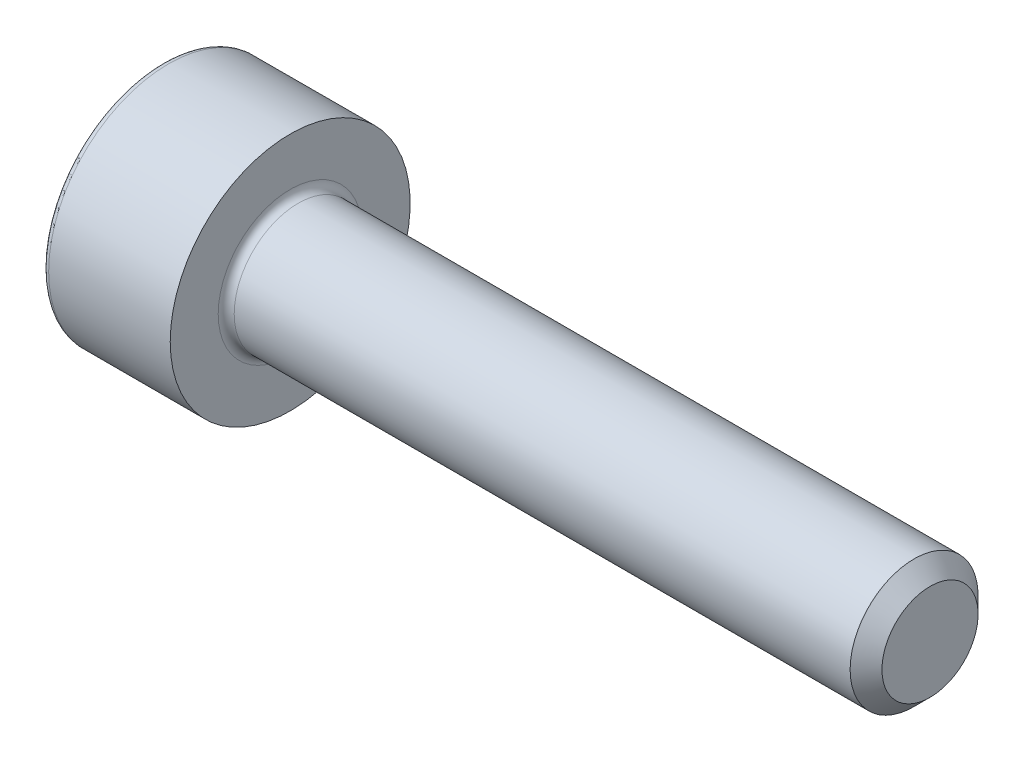
SolidWorks part; units mm, degrees
ref_plane "Front Plane" through (0, 0, 0) normal (0, 0, 1) x (1, 0, 0)
ref_plane "Top Plane" through (0, 0, 0) normal (0, 1, 0) x (1, 0, 0)
ref_plane "Right Plane" through (0, 0, 0) normal (1, 0, 0) x (0, 0, -1)
sketch "BodySke" plane through (0, 0, 0) normal (0, 0, 1) x (1, 0, 0)
  line L0 (0, 0) -> (5.8492, 0) construction
  line L1 (0, 0) -> (0, 1.5)
  line L2 (0, 1.5) -> (1.6, 1.5)
  line L3 (1.6, 1.5) -> (1.6, 0.8)
  line L4 (1.6, 0.8) -> (9.401, 0.8)
  line L5 (9.401, 0.8) -> (9.6, 0.601)
  line L6 (9.6, 0.601) -> (9.6, 0)
  line L7 (9.6, 0) -> (0, 0)
  line L8 (1.6, 0) -> (1.6, 0.601) construction
  line L9 (1.95, 1.5877) -> (1.95, 0.9267) construction
  dimension "Thread_length" = 8
  dimension "Diameter" = 1.6
  dimension "Thread_minor" = 1.202
  dimension "Body_chamfer_angle" = 45
  dimension "Length" = 8
  dimension "Head_diameter" = 3
  dimension "Head_length" = 1.6
  dimension "Advance" = 0.35
revolve "BaseBody" add sketch "BodySke" angle 360 about L0
cosmetic thread "ThreadCosmetic" [suppressed] parameters "Thread_length"=8, "Thread_minor"=1.202
fillet "Fillet1" radius 0.1 1 edges at (1.6, 0, 0.8)
fillet "Fillet2" radius 0.08 1 edges at (0, 0, 1.5)
sketch "HexSke" plane through (0, 0, 0) normal (1, 0, 0) x (0, 0, -1)
  line L1 (0, 0.866) -> (-0.75, 0.433)
  line L2 (-0.75, 0.433) -> (-0.75, -0.433)
  line L3 (-0.75, -0.433) -> (0, -0.866)
  line L4 (0, -0.866) -> (0.75, -0.433)
  line L5 (0.75, -0.433) -> (0.75, 0.433)
  line L6 (0.75, 0.433) -> (0, 0.866)
  circle A0 centre (0, 0) radius 0.75 construction
  dimension "Hex_size" = 1.5
extrude "Hex" cut sketch "HexSke" along normal blind 0.7
sketch "Hex-PreBroachSke" plane through (0, 0, 0) normal (0, 0, 1) x (1, 0, 0)
  line L0 (0, 0) -> (4.7325, 0) construction
  line L1 (0, 1.42) -> (0, -1.42) construction
  line L2 (0, 0) -> (0, 0.75)
  line L3 (0, 0.75) -> (0.7, 0.75)
  line L4 (0.7, 0.75) -> (1.133, 0)
  line L5 (1.133, 0) -> (0, 0)
  dimension "Hex_depth" = 0.7
  dimension "D1" = 1.5
  dimension "Angle" = 60
revolve "Hex-PreBroach" cut sketch "Hex-PreBroachSke" angle 360 about L0
sketch "ThdSchSke" plane through (0, 0, 0) normal (0, 0, 1) x (1, 0, 0)
  line L0 (0, 0) -> (4.4125, 0) construction
  line L1 (0, 1.42) -> (0, -1.42) construction
  line L2 (9.051, 1.0298) -> (9.051, 0.8)
  line L3 (9.051, 1.0298) -> (9.2808, 1.0298)
  line L4 (9.2808, 1.0298) -> (9.2808, 0.8)
  line L5 (9.2808, 0.8) -> (9.1659, 0.601)
  line L6 (9.1659, 0.601) -> (9.051, 0.8)
  dimension "D1" = 0.35
revolve "ThreadSchematic" [suppressed] cut sketch "ThdSchSke" angle 360 about L0
pattern_linear "ThdSchPat" [suppressed]
scale "Scale1" scale about centroid uniform scaling yes scale factor 2.5
equation "\"Thread_length@ThreadCosmetic\" = \"Thread_length@BodySke\""
equation "\"Thread_minor@ThreadCosmetic\" = \"Thread_minor@BodySke\""
equation "\"Hex_depth@Hex-PreBroachSke\" = \"Hex_length@Hex\""
equation "\"D1@Hex-PreBroachSke\" = \"Hex_size@HexSke\""
equation "\"D1@ThdSchSke\" = \"Advance@BodySke\""
equation "\"Advance@ThdSchPat\" = \"Advance@BodySke\""
equation "\"Tooth_Num@ThdSchPat\" =  int( \"Thread_length@BodySke\" / \"Advance@BodySke\" )  - 1"
